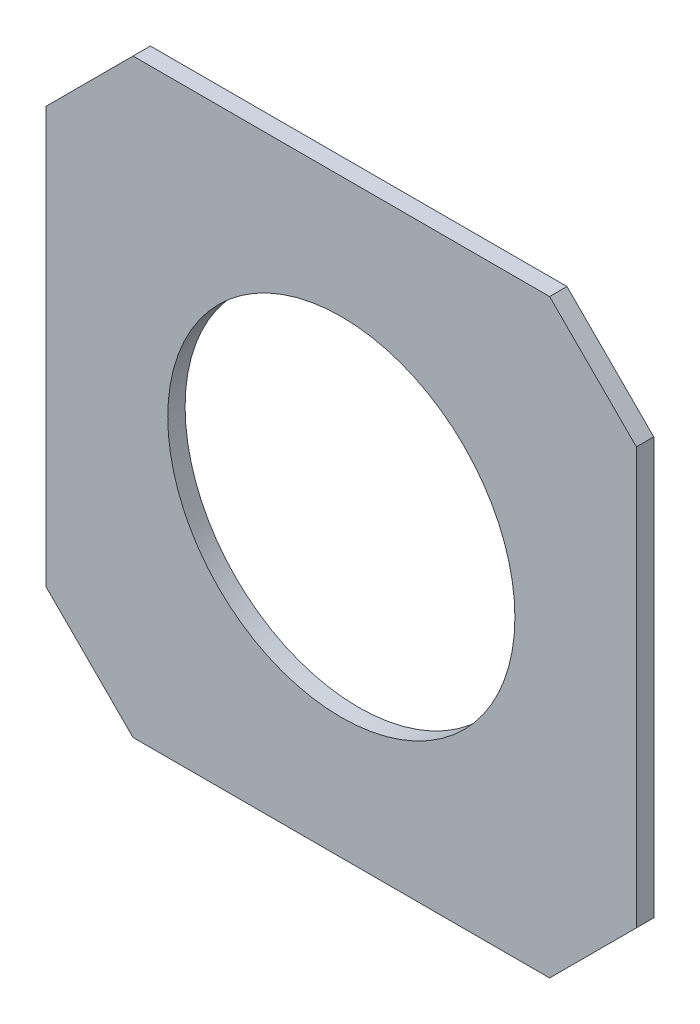
SolidWorks part; units mm, degrees
ref_plane "Front Plane" through (0, 0, 0) normal (0, 0, 1) x (1, 0, 0)
ref_plane "Top Plane" through (0, 0, 0) normal (0, 1, 0) x (1, 0, 0)
ref_plane "Right Plane" through (0, 0, 0) normal (1, 0, 0) x (0, 0, -1)
sketch "Sketch3" plane through (0, 0, 0) normal (0, 0, 1) x (1, 0, 0)
  line L0 (0, 0) -> (17, 0)
  line L1 (17, 0) -> (17, -17)
  line L2 (17, -17) -> (0, -17)
  line L3 (0, -17) -> (0, 0)
  point P0 (0, 0)
  dimension "D1" = 17
  dimension "D2" = 17
extrude "Boss-Extrude1" add sketch "Sketch3" along normal blind 0.5
sketch "Sketch4" plane through (0, 0, 0.5) normal (0, 0, 1) x (1, 0, 0)
  line L0 (2.5, 0) -> (0, -2.5)
  line L1 (17, 0) -> (0, 0) construction
  line L2 (0, 0) -> (0, -17) construction
  line L3 (8.5, 0) -> (8.5, -17) construction
  line L4 (0, -17) -> (17, -17) construction
  line L5 (0, -8.5) -> (17, -8.5) construction
  line L6 (17, -17) -> (17, 0) construction
  line L7 (14.5, 0) -> (17, -2.5)
  line L8 (14.5, -17) -> (17, -14.5)
  line L9 (2.5, -17) -> (0, -14.5)
  circle A0 centre (8.5, -8.5) radius 5
  line M6 (17, -17) -> (17, 0)
  line M7 (17, 0) -> (0, 0)
  line M8 (0, 0) -> (0, -17)
  line M9 (0, -17) -> (17, -17)
  dimension "D3" = 10
  dimension "D1" = 2.5
  dimension "D2" = 2.5
extrude "Cut-Extrude1" cut sketch "Sketch4" against normal through all contours A0 | L7 M7 M6 | L0 M7 M8 | L9 M9 M8 | L8 M9 M6
